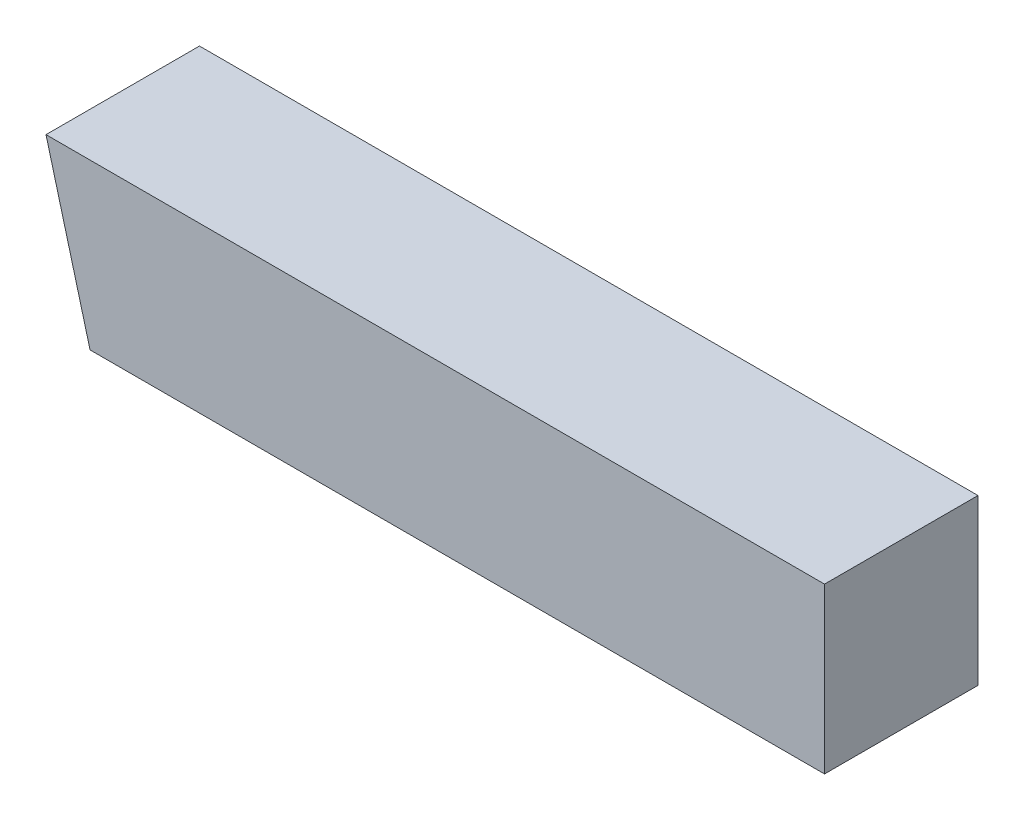
SolidWorks part; units mm, degrees
ref_plane "Front Plane" through (0, 0, 0) normal (0, 0, 1) x (1, 0, 0)
ref_plane "Top Plane" through (0, 0, 0) normal (0, 1, 0) x (1, 0, 0)
ref_plane "Right Plane" through (0, 0, 0) normal (1, 0, 0) x (0, 0, -1)
sketch "Sketch1" plane through (0, 0, 0) normal (0, 0, 1) x (1, 0, 0)
  line L0 (0, 0) -> (-170.18, 0)
  line L1 (-170.18, 0) -> (-180.3889, 38.1)
  line L2 (-180.3889, 38.1) -> (0, 38.1)
  line L3 (0, 38.1) -> (0, 0)
  line L4 (-38.1, 17.78) -> (-162.56, 17.78) construction
  circle A0 centre (-162.56, 17.78) radius 21.59 construction
  circle A1 centre (-38.1, 17.78) radius 21.59 construction
  dimension "D7" = 43.18
  dimension "D1" = 105
  dimension "D2" = 170.18
  dimension "D3" = 38.1
  dimension "D4" = 124.46
  dimension "D5" = 17.78
  dimension "D6" = 38.1
extrude "Boss-Extrude1" add sketch "Sketch1" along normal blind 35.56
sketch "Sketch2" plane through (0, 0, 0) normal (0, 0, 1) x (1, 0, 0)
  line L0 (-177.8, 38.1) -> (-177.8, 0) construction
  line L1 (-180.3889, 38.1) -> (0, 38.1) construction
  line L2 (-177.8, 0) -> (-170.18, 0) construction
  circle A0 centre (-162.56, 17.78) radius 14.3
  circle A1 centre (-38.1, 17.78) radius 14.3
  circle A2 centre (-121.92, 31.75) radius 7.15
  circle A3 centre (-132.08, 12.7) radius 6.35
  dimension "D1" = 28.6
  dimension "D2" = 28.6
  dimension "D8" = 12.7
  dimension "D9" = 14.3
  dimension "D3" = 15.24
  dimension "D4" = 45.72
  dimension "D5" = 55.88
  dimension "D6" = 31.75
  dimension "D7" = 12.7
equation "\"D2@Sketch2\"=28.6mm"
equation "\"D9@Sketch2\"=14.3mm"
